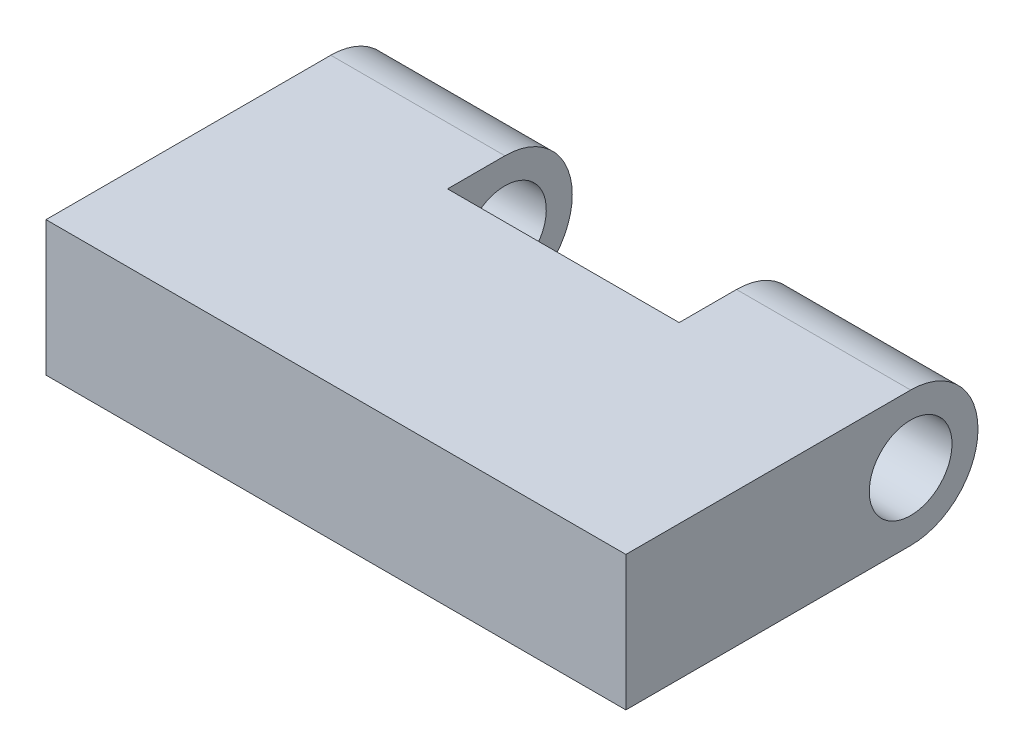
SolidWorks part; units mm, degrees
ref_plane "Front Plane" through (0, 0, 0) normal (0, 0, 1) x (1, 0, 0)
ref_plane "Top Plane" through (0, 0, 0) normal (0, 1, 0) x (1, 0, 0)
ref_plane "Right Plane" through (0, 0, 0) normal (1, 0, 0) x (0, 0, -1)
sketch "Sketch2" plane through (6.0597, 0, 0) normal (1, 0, 0) x (0, 0, -1)
  line L0 (2.3986, 21.4442) -> (-3.3687, 21.4442)
  line L2 (-3.3687, 13.7098) -> (2.3986, 13.7098)
  line L4 (-3.3687, 21.4442) -> (-13.9538, 21.4442)
  line L6 (-3.3687, 13.7098) -> (-13.9538, 13.7098)
  line L7 (-13.9538, 21.4442) -> (-13.9538, 13.7098)
  arc A0 (2.3986, 13.7098) -> (2.3986, 21.4442) centre (2.3986, 17.577) ccw
  circle A1 centre (2.3986, 17.577) radius 2.3755
  dimension "D1" = 4.7511
extrude "Boss-Extrude1" add sketch "Sketch2" along normal blind 10
ref_plane "Plane1" through (-0.5898, 0, 0) normal (1, 0, 0) x (0, 0, -1)
mirror "Mirror2" about plane through (-0.5898, 0, 0) normal (1, 0, 0) of bodies 101
sketch "Sketch3" plane through (6.0597, 0, 0) normal (-1, 0, 0) x (0, 0, 1)
  line L0 (-2.3986, 21.4442) -> (13.9538, 21.4442) construction
  line L1 (13.9538, 13.7098) -> (0.8949, 13.7098)
  line L2 (13.9538, 13.7098) -> (13.9538, 21.4442)
  line L3 (13.9538, 21.4442) -> (0.8949, 21.4442)
  line L4 (0.8949, 13.7098) -> (0.8949, 21.4442)
extrude "Boss-Extrude2" add sketch "Sketch3" along normal up to surface (13.299 mm away) up to face at (-7.2393, 17.577, 4.8108)
